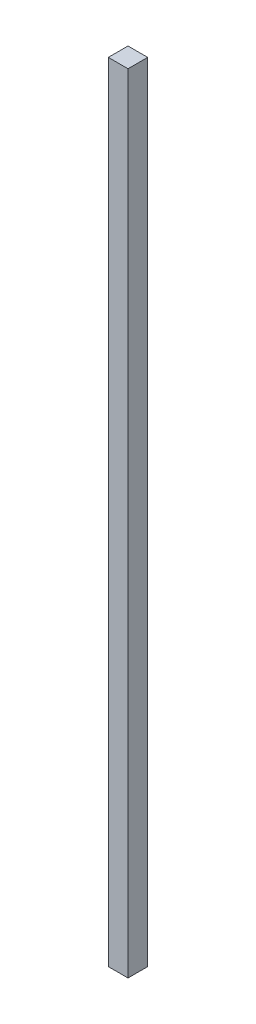
SolidWorks part; units mm, degrees
ref_plane "Front Plane" through (0, 0, 0) normal (0, 0, 1) x (1, 0, 0)
ref_plane "Top Plane" through (0, 0, 0) normal (0, 1, 0) x (1, 0, 0)
ref_plane "Right Plane" through (0, 0, 0) normal (1, 0, 0) x (0, 0, -1)
sketch "Sketch1" plane through (0, 0, 0) normal (0, 1, 0) x (1, 0, 0)
  line L1 (0, 0) -> (-25, 0)
  line L2 (0, 0) -> (0, -25)
  line L3 (0, -25) -> (-25, -25)
  line L4 (-25, 0) -> (-25, -25)
  dimension "D1" = 25
  dimension "D2" = 25
extrude "Boss-Extrude1" add sketch "Sketch1" along normal blind 1000
